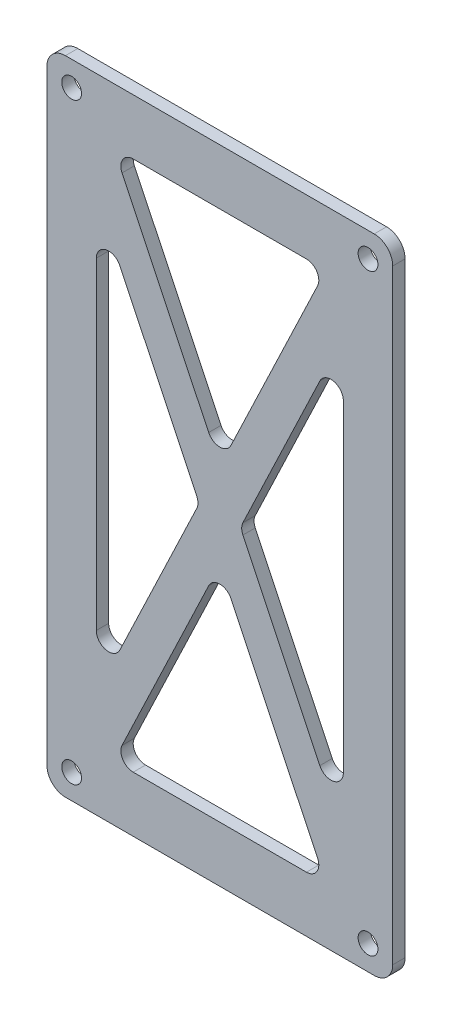
SolidWorks part; units mm, degrees
ref_plane "前视基准面" through (0, 0, 0) normal (0, 0, 1) x (1, 0, 0)
ref_plane "上视基准面" through (0, 0, 0) normal (0, 1, 0) x (1, 0, 0)
ref_plane "右视基准面" through (0, 0, 0) normal (1, 0, 0) x (0, 0, -1)
sketch "草图1" plane through (0, 0, 0) normal (0, 0, 1) x (1, 0, 0)
  line L0 (0, 48) -> (0, -48) construction
  line L1 (-24, 48) -> (24, 48) construction
  line L2 (-24, 48) -> (-24, -48) construction
  line L3 (-24, -48) -> (24, -48) construction
  line L4 (24, 48) -> (24, -48) construction
  line L5 (-24, 48) -> (24, -48) construction
  line L6 (-24, -48) -> (24, 48) construction
  line L8 (-28, 52) -> (28, 52)
  line L9 (-28, 52) -> (-28, -52)
  line L10 (-28, -52) -> (28, -52)
  line L11 (28, 52) -> (28, -52)
  line L12 (-28, 52) -> (28, -52) construction
  line L13 (-28, -52) -> (28, 52) construction
  circle A0 centre (-24, 48) radius 1.6
  circle A1 centre (-24, -48) radius 1.6
  circle A2 centre (24, -48) radius 1.6
  circle A3 centre (24, 48) radius 1.6
  point P0 (0, 0)
  point P12 (0, 0)
  dimension "D3" = 3.2
  dimension "D4" = 3.2
  dimension "D1" = 96
  dimension "D2" = 48
  dimension "D5" = 104
  dimension "D6" = 56
extrude "凸台-拉伸1" add sketch "草图1" along normal blind 2
fillet "圆角1" radius 3 4 edges at (28, -52, 1) (-28, -52, 1) (-28, 52, 1) (28, 52, 1)
sketch "草图2" plane through (0, 0, 2) normal (0, 0, 1) x (1, 0, 0)
  line L0 (-20, 34.9398) -> (-20, -34.9398)
  line L1 (-21, 44) -> (21, 44) construction
  line L2 (-21, 44) -> (-21, -44) construction
  line L3 (-21, -44) -> (21, -44) construction
  line L4 (21, 44) -> (21, -44) construction
  line L5 (-21, 44) -> (21, -44) construction
  line L6 (-21, -44) -> (21, 44) construction
  line L7 (-20, -34.9398) -> (-3.3242, 0)
  line L8 (-3.3242, 0) -> (-20, 34.9398)
  line L9 (-17.1986, -43) -> (17.1986, -43)
  line L10 (17.1986, -43) -> (0, -6.9649)
  line L11 (0, -6.9649) -> (-17.1986, -43)
  line L12 (0, 0) -> (21, 0) construction
  line L13 (0, 0) -> (0, 44) construction
  line L14 (0, 6.9649) -> (-17.1986, 43)
  line L15 (17.1986, 43) -> (0, 6.9649)
  line L16 (-17.1986, 43) -> (17.1986, 43)
  line L17 (3.3242, 0) -> (20, 34.9398)
  line L18 (20, -34.9398) -> (3.3242, 0)
  line L19 (20, 34.9398) -> (20, -34.9398)
  point P0 (0, 0)
  dimension "D1" = 42
  dimension "D2" = 88
  dimension "D3" = 2
  dimension "D4" = 3
  dimension "D5" = 3
  dimension "D6" = 3
  dimension "D7" = 1
  dimension "D8" = 3
extrude "切除-拉伸1" cut sketch "草图2" against normal blind 10
fillet "圆角2" radius 2 12 edges at (-3.3242, 0, 1) (-20, -34.9398, 1) (20, 34.9398, 1) (20, -34.9398, 1) (3.3242, 0, 1) (-17.1986, 43, 1) (17.1986, 43, 1) (0, 6.9649, 1) (17.1986, -43, 1) (-17.1986, -43, 1) (0, -6.9649, 1) (-20, 34.9398, 1)
